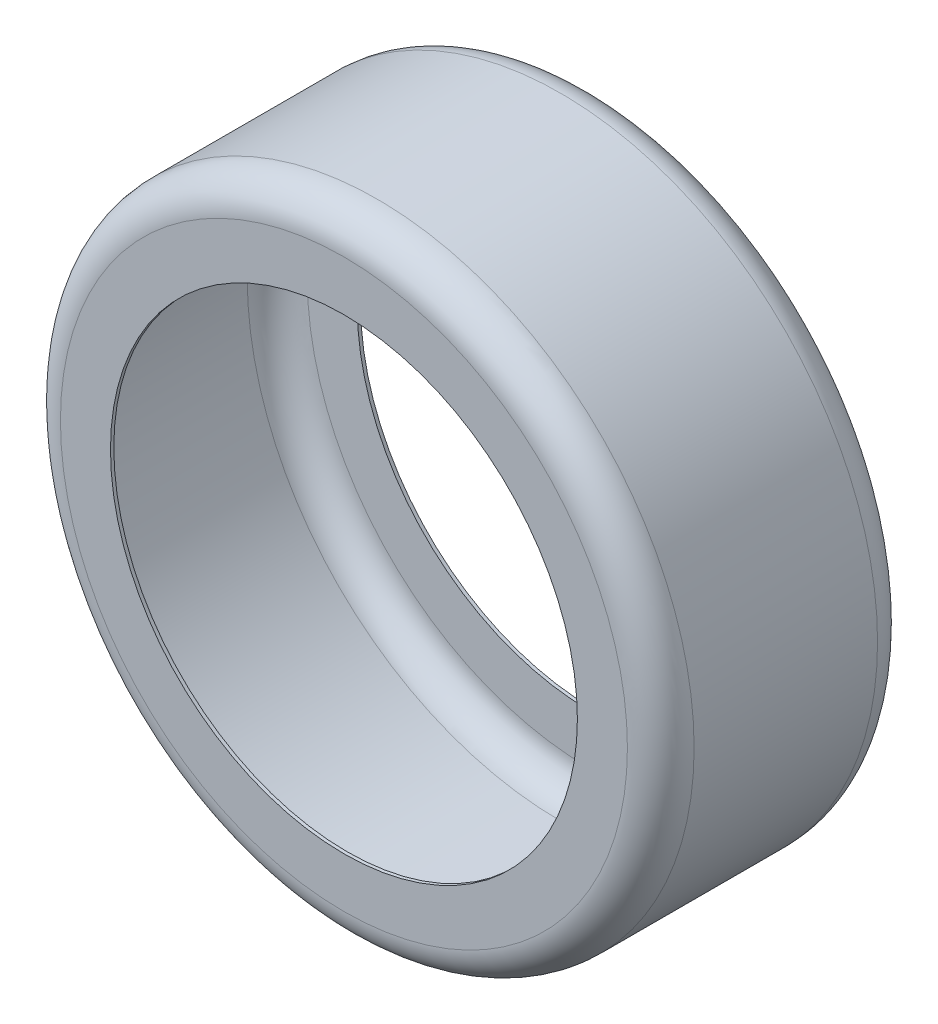
SolidWorks part; units mm, degrees
ref_plane "Front Plane" through (0, 0, 0) normal (0, 0, 1) x (1, 0, 0)
ref_plane "Top Plane" through (0, 0, 0) normal (0, 1, 0) x (1, 0, 0)
ref_plane "Right Plane" through (0, 0, 0) normal (1, 0, 0) x (0, 0, -1)
sketch "Sketch1" plane through (0, 0, 0) normal (0, 0, 1) x (1, 0, 0)
  circle A0 centre (0, 0) radius 140
  circle A1 centre (0, 0) radius 190
  dimension "D1" = 280
  dimension "D2" = 380
extrude "Boss-Extrude1" add sketch "Sketch1" along normal mid plane 150
fillet "Fillet2" radius 20 2 edges at (190, 0, 75) (190, 0, -75)
shell "Shell1" thickness 2
